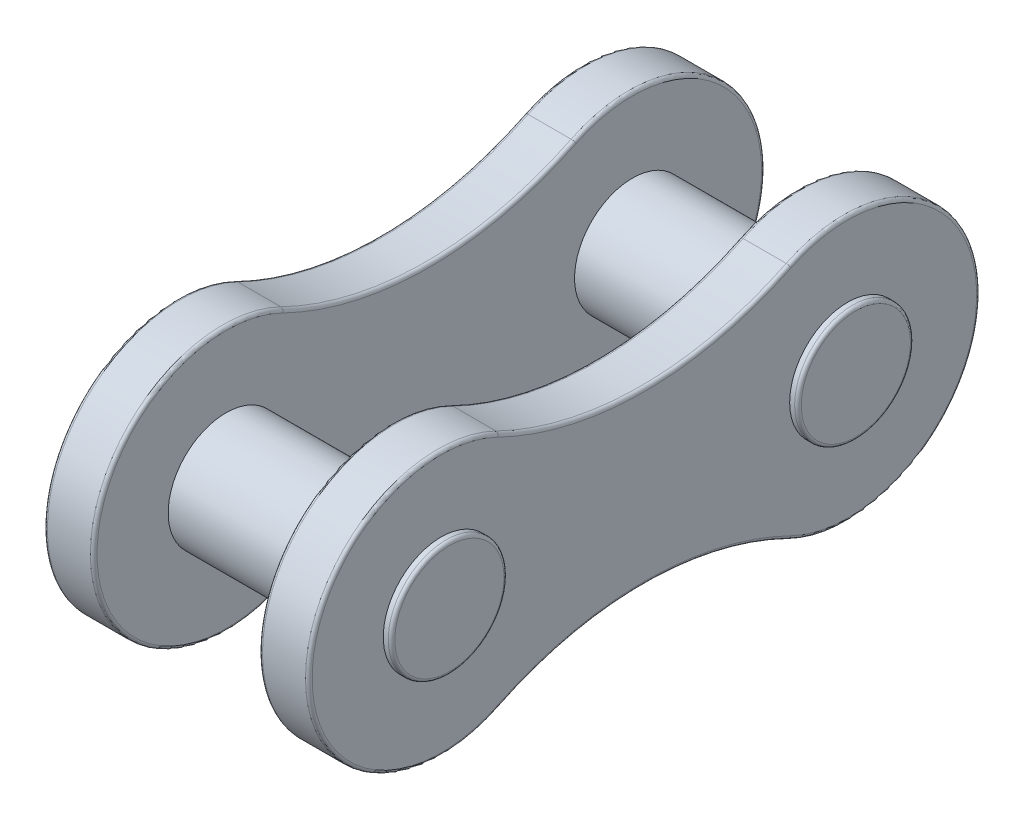
SolidWorks part; units mm, degrees
ref_plane "Front Plane" through (0, 0, 0) normal (0, 0, 1) x (1, 0, 0)
ref_plane "Top Plane" through (0, 0, 0) normal (0, 1, 0) x (1, 0, 0)
ref_plane "Right Plane" through (0, 0, 0) normal (1, 0, 0) x (0, 0, -1)
sketch "Sketch1" plane through (0, 0, 0) normal (1, 0, 0) x (0, 0, -1)
  line L0 (0, 0) -> (0, 3.5744) construction
  line L1 (-6.1406, 0) -> (6.2094, 0) construction
  circle A0 centre (-6.1406, 0) radius 1.75
  arc A1 (-4.3862, 3.5947) -> (-4.3862, -3.5947) centre (-6.1406, 0) ccw
  arc A2 (4.3862, 3.5947) -> (4.3862, -3.5947) centre (6.1406, 0) cw
  circle A3 centre (6.1406, 0) radius 1.75
  arc A4 (-4.3862, 3.5947) -> (4.3862, 3.5947) centre (0, 12.5814) ccw
  arc A5 (-4.3862, -3.5947) -> (4.3862, -3.5947) centre (0, -12.5814) cw
  dimension "D2" = 3.5
  dimension "D3" = 8
  dimension "D4" = 10
  dimension "D1" = 12.35
extrude "Boss-Extrude1" add sketch "Sketch1" along normal blind 1.5 from offset 2.5
sketch "Sketch2" plane through (0, 0, 0) normal (1, 0, 0) x (0, 0, -1)
  circle A0 centre (6.1406, 0) radius 1.75 construction
  circle A1 centre (-6.1406, 0) radius 1.75 construction
  circle A2 centre (6.1406, 0) radius 1.75
  circle A3 centre (-6.1406, 0) radius 1.75
  arc A4 (-4.3862, 3.5947) -> (4.3862, 3.5947) centre (0, 12.5814) ccw
  arc A5 (-4.3862, 3.5947) -> (-4.3862, -3.5947) centre (-6.1406, 0) ccw
  arc A6 (4.3862, -3.5947) -> (-4.3862, -3.5947) centre (0, -12.5814) ccw
  arc A7 (4.3862, -3.5947) -> (4.3862, 3.5947) centre (6.1406, 0) ccw
  arc A8 (-4.3862, 3.5947) -> (4.3862, 3.5947) centre (0, 12.5814) ccw
  arc A9 (-4.3862, 3.5947) -> (-4.3862, -3.5947) centre (-6.1406, 0) ccw
  arc A10 (4.3862, -3.5947) -> (-4.3862, -3.5947) centre (0, -12.5814) ccw
  arc A11 (4.3862, -3.5947) -> (4.3862, 3.5947) centre (6.1406, 0) ccw
  dimension "D1" = 0
extrude "Boss-Extrude2" add sketch "Sketch2" against normal blind 1.5 from offset 2.5 separate body offset against normal yes
sketch "Sketch3" plane through (0, 0, 0) normal (1, 0, 0) x (0, 0, -1)
  circle A0 centre (6.1406, 0) radius 1.75 construction
  circle A1 centre (-6.1406, 0) radius 1.75 construction
  circle A2 centre (6.1406, 0) radius 1.75
  circle A3 centre (-6.1406, 0) radius 1.75
extrude "Boss-Extrude3" add sketch "Sketch3" along normal mid plane 8.5
fillet "Fillet1" radius 0.1 20 edges at (-4, 0, -10.1406) (-4, -2.5814, 0) (-4, 0, 10.1406) (-2.5, 0, -10.1406) (-2.5, -2.5814, 0) (-2.5, 0, 10.1406) (2.5, 0, -10.1406) (2.5, -2.5814, 0) (2.5, 0, 10.1406) (4, 0, -10.1406) (4, -2.5814, 0) (4, 0, 10.1406) (-4.25, 0, -7.8906) (-4.25, 0, 4.3906) (4.25, 0, -7.8906) (4.25, 0, 4.3906) (-4, 2.5814, 0) (-2.5, 2.5814, 0) (2.5, 2.5814, 0) (4, 2.5814, 0)
